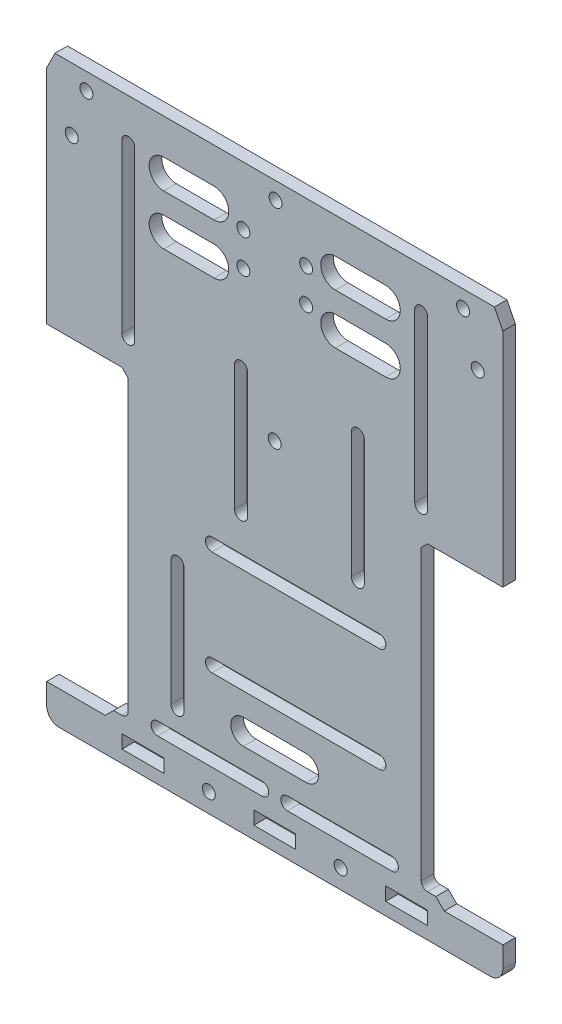
SolidWorks part; units mm, degrees
ref_plane "Plano frontal" through (0, 0, 0) normal (0, 0, 1) x (1, 0, 0)
ref_plane "Plano superior" through (0, 0, 0) normal (0, 1, 0) x (1, 0, 0)
ref_plane "Plano direito" through (0, 0, 0) normal (1, 0, 0) x (0, 0, -1)
sketch "Esboço1" plane through (0, 0, 0) normal (0, 0, 1) x (1, 0, 0)
  line L0 (0, 82) -> (0, 135)
  line L1 (3, 0) -> (106, 0)
  line L2 (0, 3) -> (0, 8)
  line L3 (2, 139) -> (107, 139)
  line L4 (109, 3) -> (109, 8)
  line L5 (0, 82) -> (18, 82)
  line L6 (109, 82) -> (109, 135)
  line L7 (0, 8) -> (14, 8)
  line L8 (19.5, 80.5) -> (19.5, 11.5)
  line L9 (109, 82) -> (91, 82)
  line L10 (95, 8) -> (93, 10)
  line L11 (109, 8) -> (95, 8)
  line L12 (89.5, 80.5) -> (89.5, 11.5)
  line L13 (93, 10) -> (91, 10)
  line L14 (14, 8) -> (16, 10)
  line L15 (16, 10) -> (18, 10)
  line L16 (91, 82) -> (89.5, 80.5)
  line L17 (18, 82) -> (19.5, 80.5)
  line L18 (109, 135) -> (107, 139)
  line L19 (0, 135) -> (2, 139)
  line L20 (26.5, 11.55) -> (51.5, 11.55) construction
  line L21 (18, 6.2) -> (28, 6.2)
  line L22 (18, 6.2) -> (18, 3)
  line L23 (18, 3) -> (28, 3)
  line L24 (28, 6.2) -> (28, 3)
  line L25 (49.5, 6.2) -> (59.5, 6.2)
  line L26 (49.5, 6.2) -> (49.5, 3)
  line L27 (49.5, 3) -> (59.5, 3)
  line L28 (59.5, 6.2) -> (59.5, 3)
  line L29 (81, 6.2) -> (91, 6.2)
  line L30 (81, 6.2) -> (81, 3)
  line L31 (81, 3) -> (91, 3)
  line L32 (91, 6.2) -> (91, 3)
  line L33 (26.5, 13.1) -> (51.5, 13.1)
  line L34 (26.5, 10) -> (51.5, 10)
  line L35 (57.5, 11.55) -> (82.5, 11.55) construction
  line L36 (57.5, 13.1) -> (82.5, 13.1)
  line L37 (57.5, 10) -> (82.5, 10)
  arc A0 (18, 10) -> (19.5, 11.5) centre (18, 11.5) ccw
  arc A1 (89.5, 11.5) -> (91, 10) centre (91, 11.5) ccw
  arc A2 (106, 0) -> (109, 3) centre (106, 3) ccw
  arc A3 (0, 3) -> (3, 0) centre (3, 3) ccw
  arc A4 (26.5, 13.1) -> (26.5, 10) centre (26.5, 11.55) ccw
  arc A5 (51.5, 10) -> (51.5, 13.1) centre (51.5, 11.55) ccw
  arc A6 (57.5, 13.1) -> (57.5, 10) centre (57.5, 11.55) ccw
  arc A7 (82.5, 10) -> (82.5, 13.1) centre (82.5, 11.55) ccw
  circle A8 centre (38.75, 4.6) radius 1.55
  circle A9 centre (70.25, 4.6) radius 1.55
  circle A10 centre (54.5, 85) radius 1.55
  circle A11 centre (6, 124) radius 1.55
  circle A12 centre (103, 124) radius 1.55
  point P44 (39, 11.55)
  point P49 (70, 11.55)
  dimension "D10" = 3
  dimension "D11" = 3
  dimension "D19" = 6
  dimension "D20" = 6
  dimension "D35" = 1.55
  dimension "D36" = 1.55
  dimension "D46" = 3.1
  dimension "D47" = 10.75
  dimension "D1" = 109
  dimension "D2" = 139
  dimension "D3" = 8
  dimension "D4" = 74
  dimension "D5" = 14
  dimension "D6" = 45
  dimension "D7" = 2
  dimension "D8" = 45
  dimension "D9" = 2
  dimension "D12" = 14
  dimension "D13" = 18
  dimension "D14" = 18
  dimension "D15" = 45
  dimension "D16" = 45
  dimension "D17" = 69
  dimension "D18" = 69
  dimension "D21" = 3
  dimension "D22" = 3
  dimension "D23" = 3.2
  dimension "D24" = 3
  dimension "D25" = 3
  dimension "D26" = 3
  dimension "D27" = 10
  dimension "D28" = 10
  dimension "D29" = 10
  dimension "D30" = 18
  dimension "D31" = 18
  dimension "D32" = 3.2
  dimension "D33" = 3.2
  dimension "D34" = 21.5
  dimension "D37" = 2
  dimension "D38" = 4
  dimension "D39" = 2
  dimension "D40" = 4
  dimension "D41" = 6
  dimension "D42" = 25
  dimension "D43" = 25
  dimension "D44" = 26.5
  dimension "D45" = 10
  dimension "D48" = 10.75
  dimension "D49" = 4.6
  dimension "D50" = 54.5
  dimension "D51" = 85
  dimension "D52" = 42
  dimension "D53" = 6
  dimension "D54" = 42
  dimension "D55" = 6
extrude "Ressalto-extrusão1" add sketch "Esboço1" along normal blind 3
sketch "Esboço2" plane through (0, 0, 3) normal (0, 0, 1) x (1, 0, 0)
  line L0 (47, 21.1) -> (62, 21.1) construction
  line L1 (47, 24.1) -> (62, 24.1)
  line L2 (47, 18.1) -> (62, 18.1)
  line L3 (19.5, 129) -> (19.5, 89) construction
  line L4 (21.05, 129) -> (21.05, 89)
  line L5 (17.95, 129) -> (17.95, 89)
  line L6 (31.25, 18.1) -> (31.25, 48.1) construction
  line L7 (29.7, 18.1) -> (29.7, 48.1)
  line L8 (32.8, 18.1) -> (32.8, 48.1)
  line L9 (74.35, 96.1) -> (74.35, 66.1) construction
  line L10 (75.9, 96.1) -> (75.9, 66.1)
  line L11 (72.8, 96.1) -> (72.8, 66.1)
  line L12 (46.45, 96.1) -> (46.45, 66.1) construction
  line L13 (48, 96.1) -> (48, 66.1)
  line L14 (44.9, 96.1) -> (44.9, 66.1)
  line L15 (28, 115) -> (40, 115) construction
  line L16 (28, 118.5) -> (40, 118.5)
  line L17 (28, 111.5) -> (40, 111.5)
  line L18 (28, 127) -> (40, 127) construction
  line L19 (28, 130.5) -> (40, 130.5)
  line L20 (28, 123.5) -> (40, 123.5)
  line L21 (19.5, 80.5) -> (19.5, 11.5) construction
  line L22 (51.5, 13.1) -> (26.5, 13.1) construction
  line L23 (49.5, 6.2) -> (49.5, 3) construction
  line L25 (89.5, 129) -> (89.5, 89) construction
  line L26 (91.05, 129) -> (91.05, 89)
  line L27 (87.95, 129) -> (87.95, 89)
  line L28 (0, 135) -> (0, 82) construction
  line L29 (69, 115) -> (81, 115) construction
  line L30 (69, 118.5) -> (81, 118.5)
  line L31 (69, 111.5) -> (81, 111.5)
  line L32 (69, 127) -> (81, 127) construction
  line L33 (69, 130.5) -> (81, 130.5)
  line L34 (107, 139) -> (2, 139) construction
  line L37 (39.5, 31.1) -> (79.5, 31.1) construction
  line L38 (69, 123.5) -> (81, 123.5)
  line L39 (109, 82) -> (109, 135) construction
  line L40 (39.5, 32.65) -> (79.5, 32.65)
  line L41 (39.5, 29.55) -> (79.5, 29.55)
  line L42 (89.5, 11.5) -> (89.5, 80.5) construction
  line L43 (39.5, 56.1) -> (79.5, 56.1) construction
  line L44 (39.5, 57.65) -> (79.5, 57.65)
  line L45 (39.5, 54.55) -> (79.5, 54.55)
  arc A0 (47, 24.1) -> (47, 18.1) centre (47, 21.1) ccw
  arc A1 (62, 18.1) -> (62, 24.1) centre (62, 21.1) ccw
  arc A2 (21.05, 129) -> (17.95, 129) centre (19.5, 129) ccw
  arc A3 (17.95, 89) -> (21.05, 89) centre (19.5, 89) ccw
  arc A4 (29.7, 18.1) -> (32.8, 18.1) centre (31.25, 18.1) ccw
  arc A5 (32.8, 48.1) -> (29.7, 48.1) centre (31.25, 48.1) ccw
  arc A6 (75.9, 96.1) -> (72.8, 96.1) centre (74.35, 96.1) ccw
  arc A7 (72.8, 66.1) -> (75.9, 66.1) centre (74.35, 66.1) ccw
  arc A8 (48, 96.1) -> (44.9, 96.1) centre (46.45, 96.1) ccw
  arc A9 (44.9, 66.1) -> (48, 66.1) centre (46.45, 66.1) ccw
  arc A10 (28, 118.5) -> (28, 111.5) centre (28, 115) ccw
  arc A11 (40, 111.5) -> (40, 118.5) centre (40, 115) ccw
  arc A12 (28, 130.5) -> (28, 123.5) centre (28, 127) ccw
  arc A13 (40, 123.5) -> (40, 130.5) centre (40, 127) ccw
  circle A14 centre (54.5, 85) radius 1.55 construction
  arc A15 (91.05, 129) -> (87.95, 129) centre (89.5, 129) ccw
  arc A16 (87.95, 89) -> (91.05, 89) centre (89.5, 89) ccw
  arc A19 (69, 118.5) -> (69, 111.5) centre (69, 115) ccw
  arc A20 (81, 111.5) -> (81, 118.5) centre (81, 115) ccw
  arc A21 (69, 130.5) -> (69, 123.5) centre (69, 127) ccw
  arc A22 (81, 123.5) -> (81, 130.5) centre (81, 127) ccw
  arc A23 (39.5, 32.65) -> (39.5, 29.55) centre (39.5, 31.1) ccw
  arc A24 (79.5, 29.55) -> (79.5, 32.65) centre (79.5, 31.1) ccw
  arc A25 (39.5, 57.65) -> (39.5, 54.55) centre (39.5, 56.1) ccw
  arc A26 (79.5, 54.55) -> (79.5, 57.65) centre (79.5, 56.1) ccw
  circle A27 centre (47, 117) radius 1.55
  circle A28 centre (47, 125) radius 1.55
  circle A29 centre (62, 117) radius 1.55
  circle A30 centre (62, 125) radius 1.55
  point P2 (54.5, 21.1)
  point P7 (19.5, 109)
  point P14 (31.25, 33.1)
  point P21 (74.35, 81.1)
  point P28 (46.45, 81.1)
  point P35 (34, 115)
  point P42 (34, 127)
  point P59 (89.5, 109)
  point P77 (75, 115)
  point P84 (75, 127)
  point P93 (59.5, 31.1)
  point P102 (59.5, 56.1)
  dimension "D1" = 1.55
  dimension "D2" = 1.55
  dimension "D3" = 1.55
  dimension "D4" = 70
  dimension "D6" = 3
  dimension "D20" = 3.5
  dimension "D21" = 3.5
  dimension "D28" = 1.55
  dimension "D34" = 3.5
  dimension "D41" = 1.55
  dimension "D42" = 10
  dimension "D43" = 10
  dimension "D44" = 40
  dimension "D45" = 10
  dimension "D46" = 1.55
  dimension "D30" = 1.55
  dimension "D35" = 3.5
  dimension "D36" = 7
  dimension "D48" = 3.1
  dimension "D52" = 3.1
  dimension "D5" = 19.5
  dimension "D7" = 15
  dimension "D8" = 11.75
  dimension "D9" = 30
  dimension "D10" = 30
  dimension "D11" = 30
  dimension "D12" = 48
  dimension "D13" = 6
  dimension "D14" = 15.2
  dimension "D15" = 8
  dimension "D16" = 27.9
  dimension "D17" = 40
  dimension "D18" = 10
  dimension "D19" = 2.5
  dimension "D22" = 12
  dimension "D23" = 12
  dimension "D24" = 12
  dimension "D25" = 28
  dimension "D26" = 30
  dimension "D27" = 12
  dimension "D29" = 40
  dimension "D31" = 12
  dimension "D32" = 12
  dimension "D33" = 28
  dimension "D37" = 7
  dimension "D40" = 40
  dimension "D47" = 25
  dimension "D49" = 8
  dimension "D51" = 2
  dimension "D53" = 8
  dimension "D55" = 2
extrude "Corte-extrusão1" cut sketch "Esboço2" against normal through all
sketch "Esboço3" plane through (0, 0, 3) normal (0, 0, 1) x (1, 0, 0)
  circle A0 centre (54.6932, 134.9373) radius 1.55
  circle A1 centre (9.5, 134.9373) radius 1.55
  circle A2 centre (99.5, 134.9373) radius 1.55
  dimension "D1" = 3.1
  dimension "D2" = 3.1
  dimension "D3" = 3.1
extrude "Corte-extrusão2" cut sketch "Esboço3" against normal blind 10
